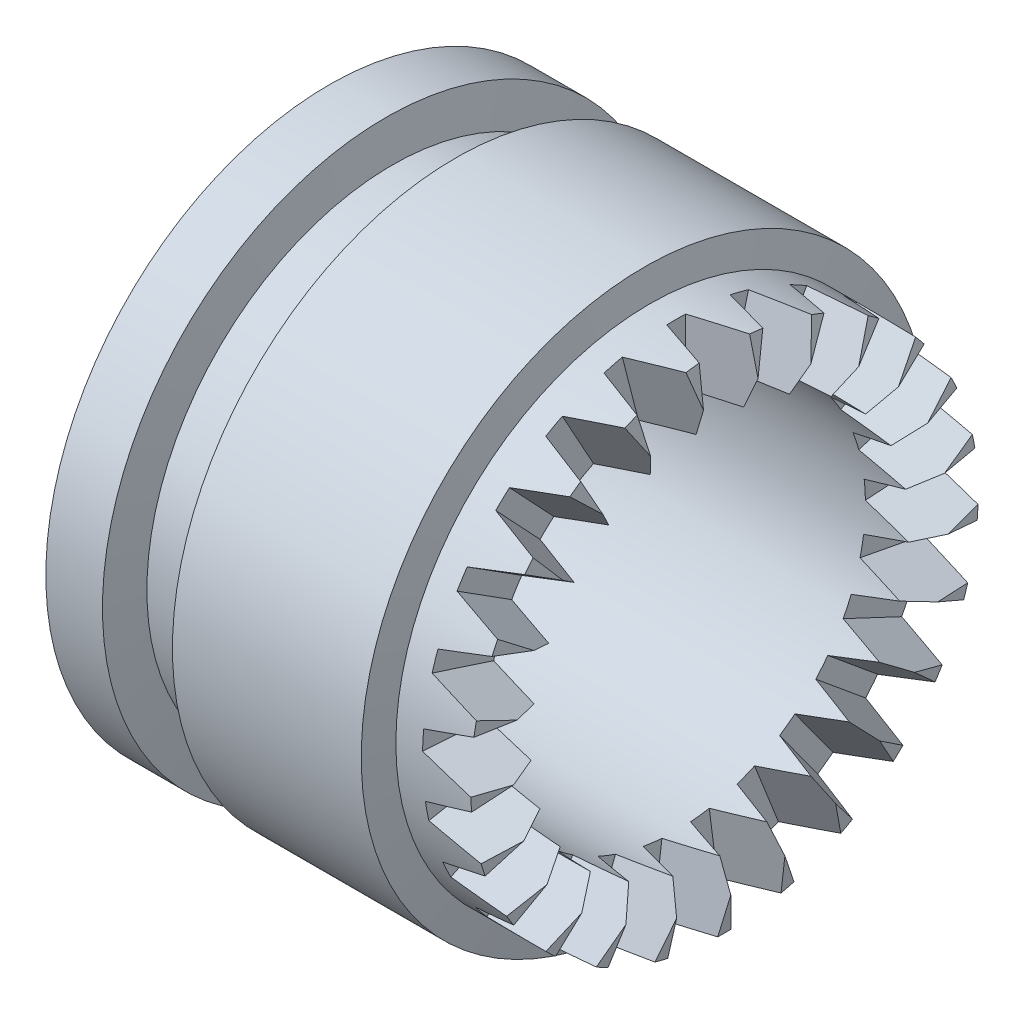
SolidWorks part; units mm, degrees
ref_plane "Front Plane" through (0, 0, 0) normal (0, 0, 1) x (1, 0, 0)
ref_plane "Top Plane" through (0, 0, 0) normal (0, 1, 0) x (1, 0, 0)
ref_plane "Right Plane" through (0, 0, 0) normal (1, 0, 0) x (0, 0, -1)
sketch "Sketch1" plane through (0, 0, 0) normal (0, 0, 1) x (1, 0, 0)
  line L0 (-31.6948, 0) -> (-53.6948, 0)
  line L1 (12.1, 0) -> (-12.1, 0) construction
  line L2 (-53.6948, 0) -> (-53.6948, 12.4176)
  line L3 (-53.2394, 15) -> (-50.2394, 15)
  line L4 (-31.6948, 10.0171) -> (-31.6948, 0)
  line L5 (-53.6948, 12.4176) -> (-53.2394, 15)
  line L6 (-50.2394, 15) -> (-49.8868, 13)
  line L7 (-49.8868, 13) -> (-46.8868, 13)
  line L8 (-46.8868, 13) -> (-46.5341, 15)
  line L9 (-36.5341, 15) -> (-36.2592, 13.4411)
  line L10 (-36.2592, 13.4411) -> (-32.2985, 13.4411)
  line L11 (-32.2985, 13.4411) -> (-31.6948, 10.0171)
  line L12 (-46.5341, 15) -> (-36.5341, 15)
  dimension "D1" = 22
  dimension "D2" = 15
  dimension "D3" = 10
  dimension "D4" = 3
  dimension "D5" = 3
  dimension "D6" = 10
  dimension "D7" = 100
  dimension "D8" = 100
  dimension "D9" = 2
  dimension "D10" = 100
  dimension "D11" = 10
revolve "Revolve1" add sketch "Sketch1" angle 360 about L0
sketch "Sketch2" plane through (-31.6948, 0, 0) normal (1, 0, 0) x (0, 0, -1)
  circle A1 centre (0, 0) radius 10.0171
  circle A2 centre (0, 0) radius 10.0171
  dimension "D1" = 0
extrude "Cut-Extrude1" cut sketch "Sketch2" against normal blind 19
sketch "Sketch3" plane through (-53.6948, 0, 0) normal (-1, 0, 0) x (0, 0, 1)
  circle A1 centre (0, 0) radius 12.4176
  circle A2 centre (0, 0) radius 12.4176
  dimension "D1" = 0
extrude "Cut-Extrude3" cut sketch "Sketch3" against normal blind 3
ref_plane "Plane1" through (-36.2592, 13.4411, 0) normal (0, 1, 0) x (1, 0, 0)
sketch "Sketch10" plane through (-36.2592, 13.4411, 0) normal (0, 1, 0) x (1, 0, 0)
  line L0 (4.5645, 0) -> (0, 0) construction
  line L1 (4.5645, 0) -> (-17.4355, 0) construction
  line L2 (3.9607, 0) -> (4.5645, 0) construction
  line L3 (0, 0) -> (3.9607, 0) construction
  line L4 (1.4104, 0.5) -> (4.5645, 1.5319)
  line L6 (4.5645, -1.5319) -> (1.4104, -0.5)
  line L7 (1.4104, -0.5) -> (1.4104, 0.5)
  line L8 (4.5645, -1.5319) -> (4.5645, 1.5319)
  line L9 (4.5645, 10.0171) -> (4.5645, -10.0171) construction
  dimension "D3" = 0.5
  dimension "D4" = 0.5
extrude "Cut-Extrude4" cut sketch "Sketch10" against normal blind 4
pattern_circular "CirPattern1" count 25 over 360 about axis through (0, 0, 0) along (1, 0, 0) of "Cut-Extrude4"
